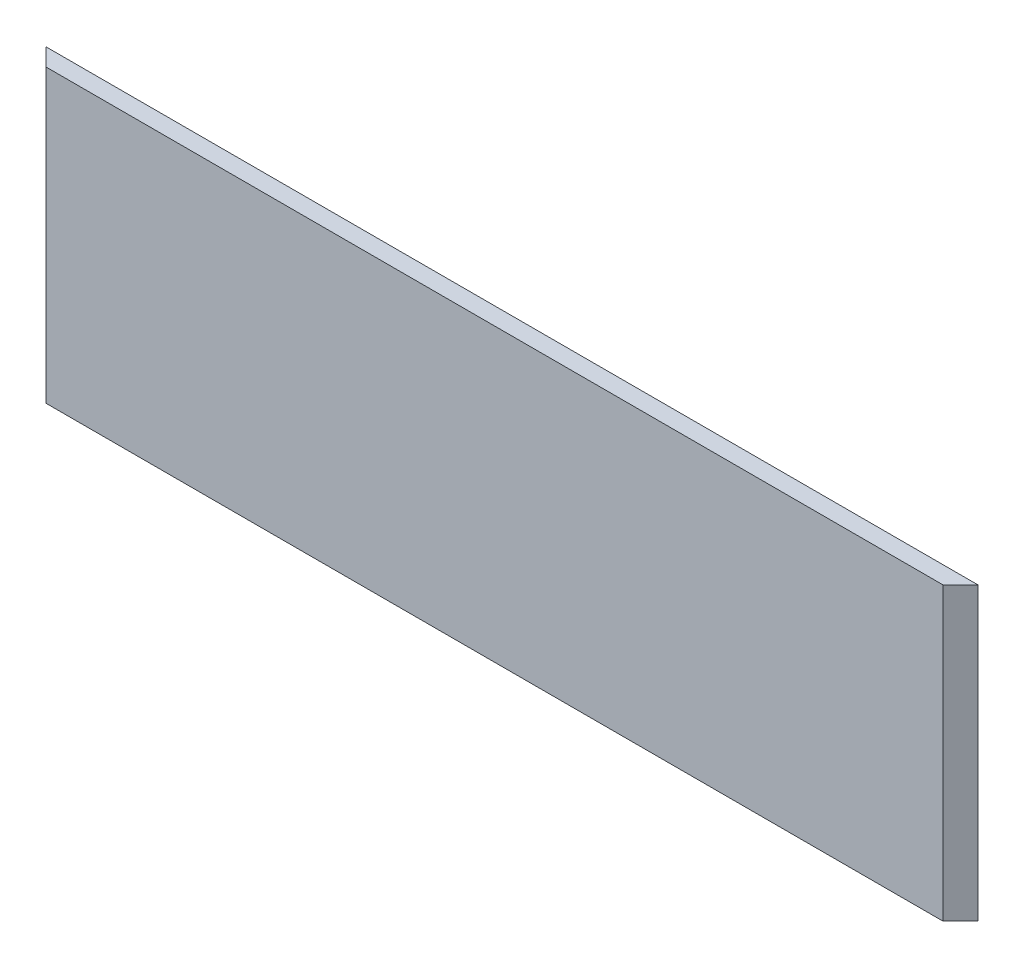
SolidWorks part; units mm, degrees
ref_plane "Front Plane" through (0, 0, 0) normal (0, 0, 1) x (1, 0, 0)
ref_plane "Top Plane" through (0, 0, 0) normal (0, 1, 0) x (1, 0, 0)
ref_plane "Right Plane" through (0, 0, 0) normal (1, 0, 0) x (0, 0, -1)
sketch "Sketch1" plane through (0, 0, 0) normal (0, 1, 0) x (1, 0, 0)
  line L1 (80, -1.5) -> (-80, -1.5)
  line L2 (80, -1.5) -> (80, 1.5)
  line L3 (80, 1.5) -> (-80, 1.5)
  line L4 (-80, -1.5) -> (-80, 1.5)
  line L5 (80, -1.5) -> (-80, 1.5) construction
  line L6 (80, 1.5) -> (-80, -1.5) construction
  point P0 (0, 0)
  dimension "D1" = 160
  dimension "D2" = 3
extrude "Boss-Extrude1" add sketch "Sketch1" along normal blind 50
sketch "Sketch3" plane through (0, 50, 0) normal (0, 1, 0) x (1, 0, 0)
  line L0 (-80, -1.5) -> (-80, 1.5)
  line L2 (-80, -1.5) -> (80, -1.5) construction
  line L3 (-77, -1.5) -> (-80, -1.5)
  line L4 (-80, 1.5) -> (-77, -1.5)
  line L5 (80, -1.5) -> (80, 1.5)
  line L7 (77, -1.5) -> (80, -1.5)
  line L8 (80, 1.5) -> (77, -1.5)
  dimension "D1" = 45
  dimension "D2" = 45
extrude "Cut-Extrude1" cut sketch "Sketch3" against normal blind 55
